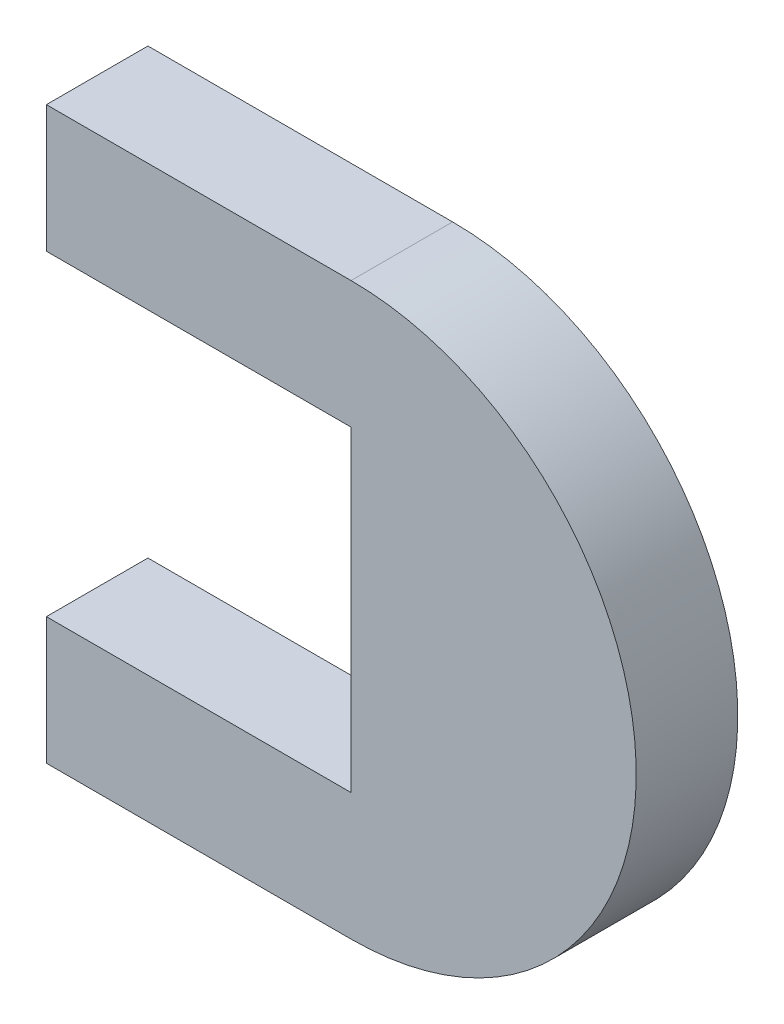
SolidWorks part; units mm, degrees
ref_plane "Front Plane" through (0, 0, 0) normal (0, 0, 1) x (1, 0, 0)
ref_plane "Top Plane" through (0, 0, 0) normal (0, 1, 0) x (1, 0, 0)
ref_plane "Right Plane" through (0, 0, 0) normal (1, 0, 0) x (0, 0, -1)
sketch "Sketch1" plane through (0, 0, 0) normal (0, 0, 1) x (1, 0, 0)
  line L0 (-30, 15.58) -> (0, 15.58)
  line L1 (-30, 15.58) -> (-30, 28.08)
  line L2 (-30, 28.08) -> (0, 28.08)
  line L3 (0, 15.58) -> (0, -15.58)
  line L4 (0, -15.58) -> (-30, -15.58)
  line L5 (-30, -15.58) -> (-30, -28.08)
  line L6 (-30, -28.08) -> (0, -28.08)
  arc A1 (0, 28.08) -> (0, -28.08) centre (0, 0) cw
  point P10 (0, 28.083)
  dimension "D1" = 31.16
  dimension "D2" = 12.5
  dimension "D3" = 30
extrude "Boss-Extrude1" add sketch "Sketch1" along normal blind 10
